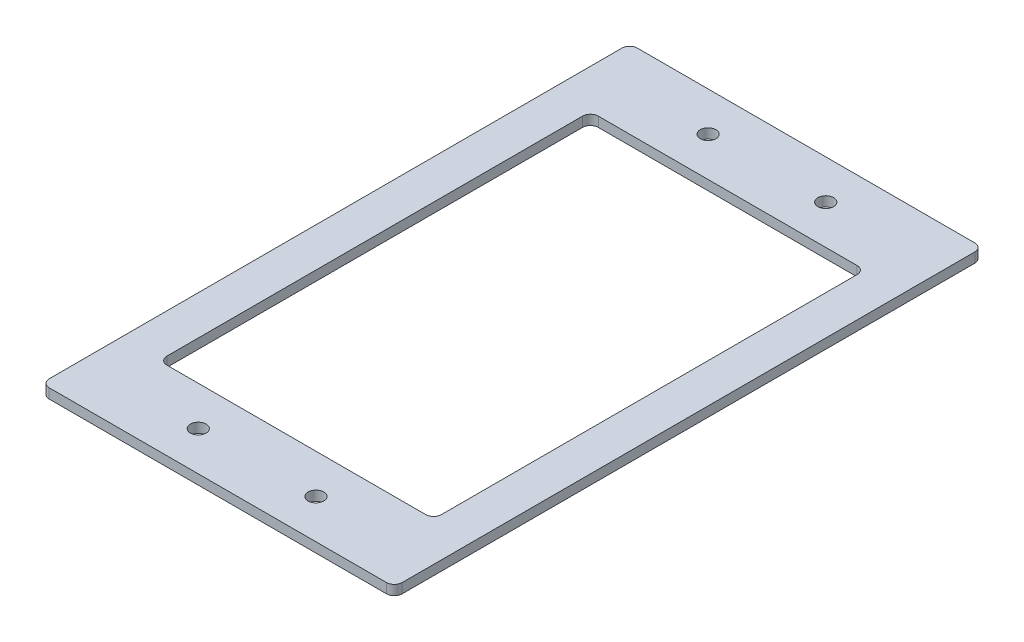
SolidWorks part; units mm, degrees
ref_plane "Front Plane" through (0, 0, 0) normal (0, 0, 1) x (1, 0, 0)
ref_plane "Top Plane" through (0, 0, 0) normal (0, 1, 0) x (1, 0, 0)
ref_plane "Right Plane" through (0, 0, 0) normal (1, 0, 0) x (0, 0, -1)
sketch "Sketch1" plane through (0, 0, 0) normal (0, 1, 0) x (1, 0, 0)
  line L1 (57.15, -95.25) -> (-57.15, -95.25)
  line L2 (57.15, -95.25) -> (57.15, 95.25)
  line L3 (57.15, 95.25) -> (-57.15, 95.25)
  line L4 (-57.15, -95.25) -> (-57.15, 95.25)
  line L5 (57.15, -95.25) -> (-57.15, 95.25) construction
  line L6 (57.15, 95.25) -> (-57.15, -95.25) construction
  line L7 (44.45, -69.85) -> (-44.45, -69.85)
  line L8 (44.45, -69.85) -> (44.45, 69.85)
  line L9 (44.45, 69.85) -> (-44.45, 69.85)
  line L10 (-44.45, -69.85) -> (-44.45, 69.85)
  line L11 (44.45, -69.85) -> (-44.45, 69.85) construction
  line L12 (44.45, 69.85) -> (-44.45, -69.85) construction
  point P0 (0, 0)
  point P6 (0, 0)
  dimension "D1" = 114.3
  dimension "D2" = 190.5
  dimension "D3" = 12.7
  dimension "D4" = 25.4
extrude "Boss-Extrude1" add sketch "Sketch1" along normal blind 3.175
sketch "Sketch2" plane through (0, 3.175, 0) normal (0, 1, 0) x (1, 0, 0)
  line L0 (-57.15, -95.25) -> (57.15, -95.25) construction
  line L1 (57.15, -95.25) -> (57.15, 95.25) construction
  line L3 (0, 0) -> (38.7987, 0) construction
  line L4 (38.7987, 0) -> (-37.1207, 0) construction
  line L5 (0, 0) -> (0, -35.6688) construction
  circle A0 centre (19.05, -82.55) radius 2.54
  circle A1 centre (19.05, 82.55) radius 2.54
  circle A2 centre (-19.05, -82.55) radius 2.54
  circle A3 centre (-19.05, 82.55) radius 2.54
  dimension "D1" = 12.7
  dimension "D2" = 5.08
  dimension "D3" = 38.1
extrude "Cut-Extrude1" cut sketch "Sketch2" against normal blind 4.7625
fillet "Fillet1" radius 2.54 4 edges at (44.45, 1.5875, -69.85) (-44.45, 1.5875, -69.85) (-44.45, 1.5875, 69.85) (44.45, 1.5875, 69.85)
fillet "Fillet2" radius 2.54 4 edges at (-57.15, 1.5875, 95.25) (-57.15, 1.5875, -95.25) (57.15, 1.5875, -95.25) (57.15, 1.5875, 95.25)
